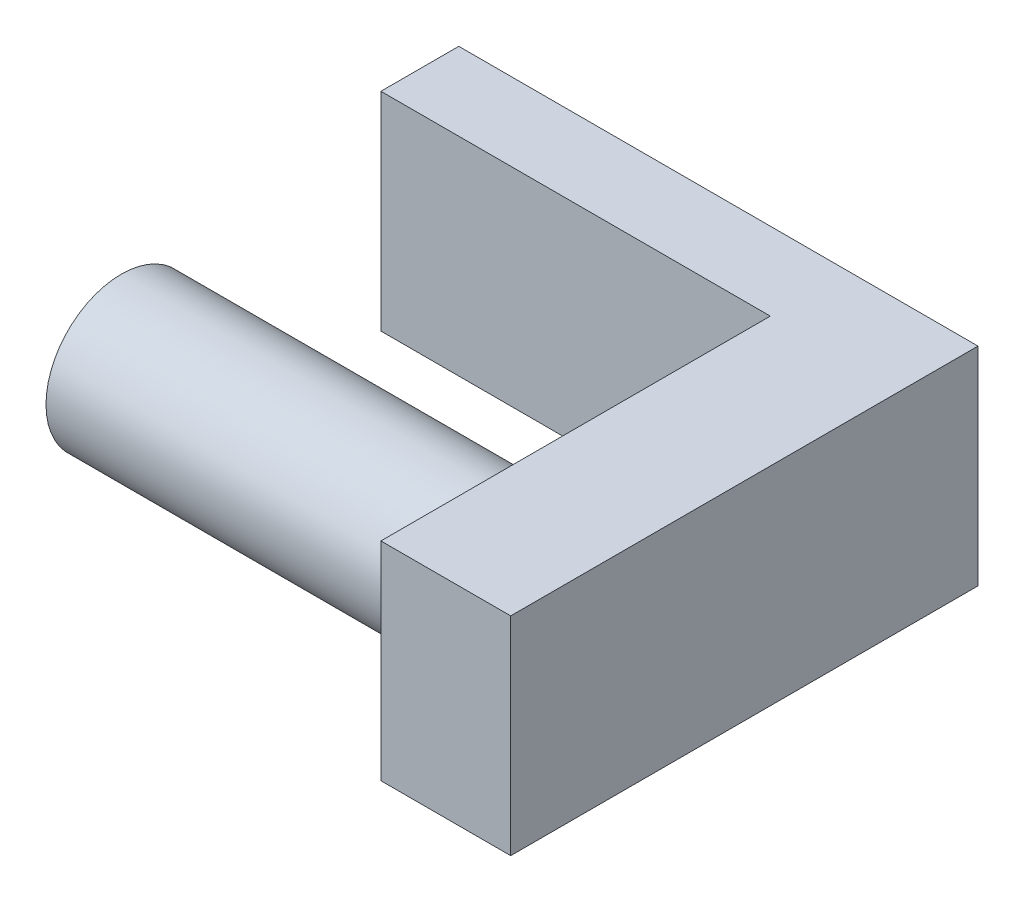
SolidWorks part; units mm, degrees
ref_plane "Plan de face" through (0, 0, 0) normal (0, 0, 1) x (1, 0, 0)
ref_plane "Plan de dessus" through (0, 0, 0) normal (0, 1, 0) x (1, 0, 0)
ref_plane "Plan de droite" through (0, 0, 0) normal (1, 0, 0) x (0, 0, -1)
sketch "Esquisse1" plane through (0, 0, 0) normal (0, 0, 1) x (1, 0, 0)
  line L1 (0, 0) -> (20, 0)
  line L2 (0, 0) -> (0, 8)
  line L3 (0, 8) -> (20, 8)
  line L4 (20, 0) -> (20, 8)
  dimension "D1" = 8
  dimension "D2" = 20
extrude "Boss.-Extru.1" add sketch "Esquisse1" along normal blind 3
sketch "Esquisse2" plane through (0, 0, 3) normal (0, 0, 1) x (1, 0, 0)
  line L0 (0, 0) -> (20, 0) construction
  line L1 (20, 8) -> (15, 8)
  line L2 (20, 8) -> (20, 0)
  line L3 (20, 0) -> (15, 0)
  line L4 (15, 8) -> (15, 0)
  dimension "D1" = 5
extrude "Boss.-Extru.2" add sketch "Esquisse2" along normal blind 15
sketch "Esquisse3" plane through (15, 0, 0) normal (-1, 0, 0) x (0, 0, 1)
  line L0 (13, 8) -> (13, 4) construction
  line L1 (18, 8) -> (3, 8) construction
  line L2 (13, 4) -> (18, 4) construction
  line L3 (18, 8) -> (18, 0) construction
  circle A0 centre (13, 4) radius 2.9
  dimension "D1" = 5.8
  dimension "D2" = 5
extrude "Boss.-Extru.3" add sketch "Esquisse3" along normal blind 15
